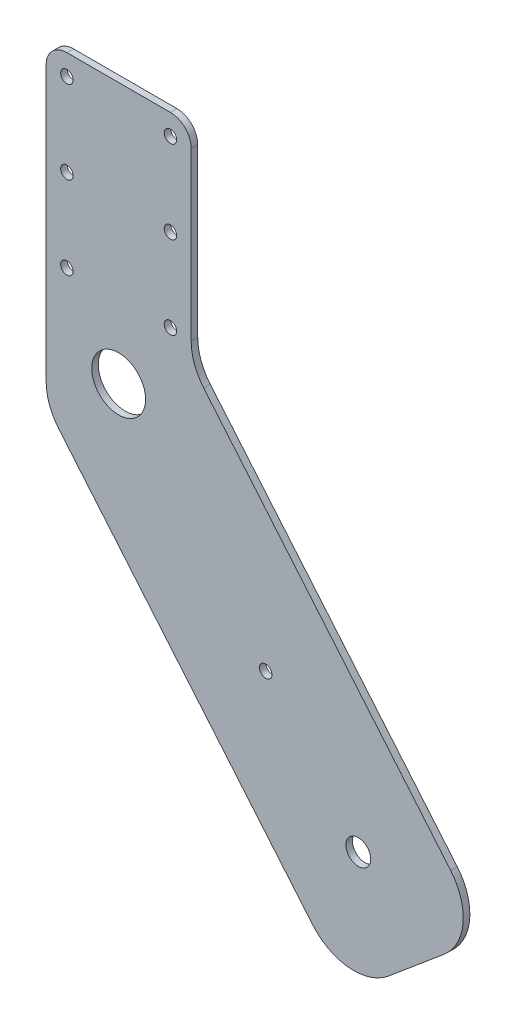
SolidWorks part; units mm, degrees
material "6061 Alloy"
ref_plane "Front Plane" through (0, 0, 0) normal (0, 0, 1) x (1, 0, 0)
ref_plane "Top Plane" through (0, 0, 0) normal (0, 1, 0) x (1, 0, 0)
ref_plane "Right Plane" through (0, 0, 0) normal (1, 0, 0) x (0, 0, -1)
sketch "Sketch1" plane through (0, 0, 0) normal (0, 0, 1) x (1, 0, 0)
  line L0 (0, 0) -> (0, 50)
  line L1 (0, 50) -> (35, 50)
  line L2 (35, 50) -> (35, 0)
  line L6 (0, 0) -> (35, 0) construction
  line L7 (5, 50) -> (5, 0) construction
  line L8 (0, 0) -> (5, 0) construction
  line L9 (5, 45) -> (5, 50) construction
  line L10 (17.5, 50) -> (17.5, -13) construction
  line L11 (0, 0) -> (0, -26)
  line L13 (0, 25) -> (5, 25) construction
  line L15 (17.5, -13) -> (17.5, 5) construction
  line L16 (17.5, 5) -> (30, 5) construction
  line L17 (17.5, -13) -> (75.3509, -81.944) construction
  line L18 (0, -26) -> (72.6686, -112.603)
  line L19 (72.6686, -112.603) -> (106.0099, -84.6263)
  line L20 (106.0099, -84.6263) -> (35, 0)
  line L21 (36.3343, -69.3015) -> (53.005, -55.3132) construction
  line L22 (53.005, -55.3132) -> (69.6756, -41.3248) construction
  line L23 (75.3509, -81.944) -> (89.3392, -98.6147) construction
  line L24 (17.5, -13) -> (17.5, -26) construction
  line L25 (17.5, -26) -> (0, -26) construction
  line L26 (17.5, -13) -> (35, -13) construction
  line L27 (35, -13) -> (35, 0) construction
  circle A0 centre (17.5, -13) radius 6.5
  circle A1 centre (5, 45) radius 1.5
  circle A2 centre (5, 25) radius 1.5
  circle A3 centre (5, 5) radius 1.5
  circle A4 centre (30, 5) radius 1.5
  circle A5 centre (30, 25) radius 1.5
  circle A6 centre (30, 45) radius 1.5
  circle A7 centre (75.3509, -81.944) radius 3
  circle A8 centre (53.005, -55.3132) radius 1.5
  dimension "D5" = 13
  dimension "D7" = 3
  dimension "D9" = 20
  dimension "D10" = 20
  dimension "D11" = 90
  dimension "D3" = 6
  dimension "D1" = 35
  dimension "D2" = 50
  dimension "D4" = 13
  dimension "D6" = 5
  dimension "D8" = 5
  dimension "D12" = 140
extrude "Boss-Extrude1" add sketch "Sketch1" along normal blind 1.5875
fillet "Fillet1" radius 5 2 edges at (0, 50, 0.7937) (35, 50, 0.7937)
fillet "Fillet2" radius 13 4 edges at (72.6686, -112.603, 0.7937) (106.0099, -84.6263, 0.7937) (35, 0, 0.7937) (0, -26, 0.7937)
